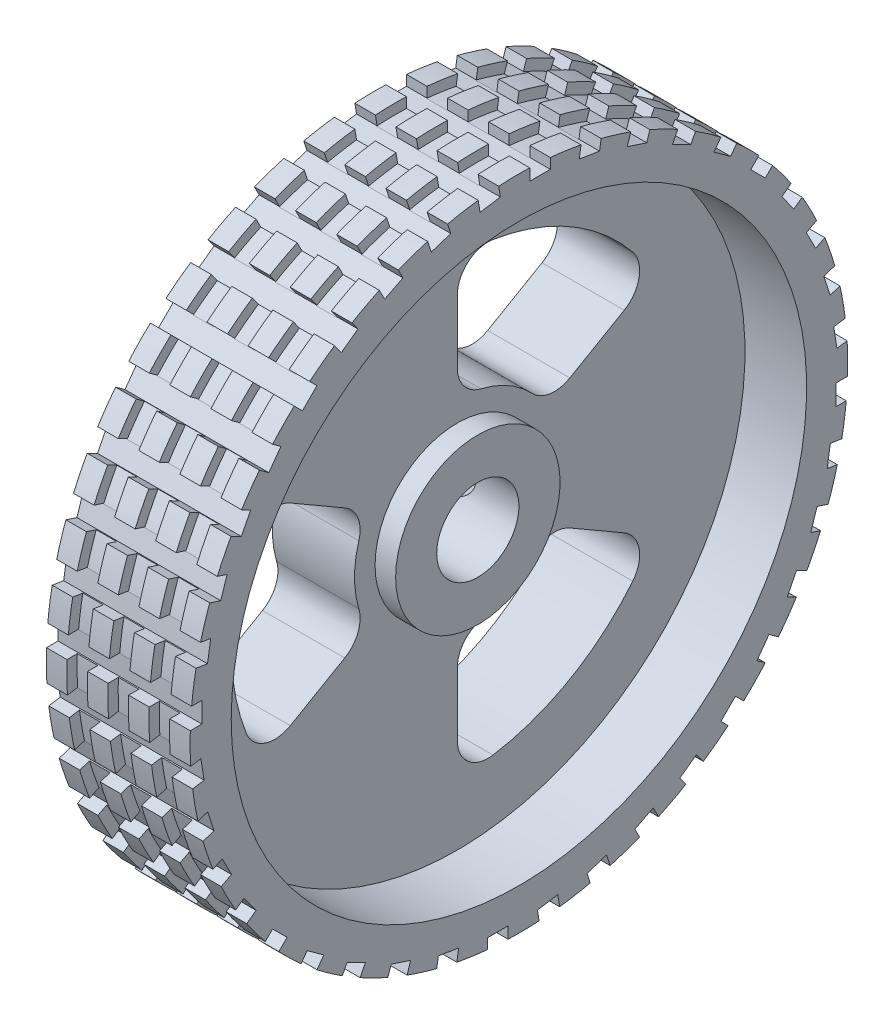
SolidWorks part; units mm, degrees
ref_plane "Front Plane" through (0, 0, 0) normal (0, 0, 1) x (1, 0, 0)
ref_plane "Top Plane" through (0, 0, 0) normal (0, 1, 0) x (1, 0, 0)
ref_plane "Right Plane" through (0, 0, 0) normal (1, 0, 0) x (0, 0, -1)
sketch "Sketch1" plane through (0, 0, 0) normal (0, 0, 1) x (1, 0, 0)
  line L0 (0, 0) -> (11.7914, 0) construction
  line L1 (0, 2) -> (5, 2)
  line L2 (5, 2) -> (5, 4)
  line L3 (5, 4) -> (4, 4)
  line L4 (4, 4) -> (4, 14)
  line L5 (4, 14) -> (7, 14)
  line L6 (7, 14) -> (7, 16)
  line L7 (7, 16) -> (0, 16)
  line L8 (0, 16) -> (0, 2)
  dimension "D1" = 7
  dimension "D2" = 4
  dimension "D3" = 4
  dimension "D4" = 8
  dimension "D5" = 5
  dimension "D6" = 28
  dimension "D7" = 32
revolve "Revolve1" add sketch "Sketch1" angle 360 about L0
sketch "Sketch2" plane through (0, 0, 0) normal (0, 1, 0) x (1, 0, 0)
  line L0 (2, 0) -> (2, 16) construction
  line L1 (7, 16) -> (0, 16) construction
  line L2 (2.9, 0) -> (2.9, 11.5)
  line L3 (0, 0) -> (7, 0) construction
  line L4 (7, -16) -> (7, 16) construction
  line L5 (2.9, 11.5) -> (3.5, 11.5)
  line L6 (3.5, 11.5) -> (3.5, 16)
  line L7 (7, 16) -> (0, 16) construction
  line L8 (3.5, 16) -> (2, 16)
  line L9 (2, 16) -> (2, 0)
  line L10 (0, 16) -> (0, -16) construction
  line L11 (2, 0) -> (2, 19.1764) construction
  line L12 (2, 0) -> (2.9, 0)
  dimension "D1" = 4.5
  dimension "D2" = 2
  dimension "D3" = 3
  dimension "D4" = 1.8
revolve "Cut-Revolve1" cut sketch "Sketch2" angle 360 about L9
sketch "Sketch4" plane through (4, 0, 0) normal (1, 0, 0) x (0, 0, -1)
  line L0 (-8.124, 4.6904) -> (-5.4772, 3.1623)
  line L1 (-8.124, -4.6904) -> (-5.4772, -3.1623)
  line L2 (0, 0) -> (-18.7263, 0) construction
  line L3 (0, 3.85) -> (0, -3.85) construction
  arc A0 (-10.2752, 3.9269) -> (-10.2752, -3.9269) centre (0, 0) ccw
  arc A2 (-10.2752, -3.9269) -> (-8.124, -4.6904) centre (-8.874, -3.3914) ccw
  circle A3 centre (0, 0) radius 5
  arc A4 (-4.7902, 1.4333) -> (-4.7902, -1.4333) centre (0, 0) ccw
  arc A5 (-10.2752, 3.9269) -> (-8.124, 4.6904) centre (-8.874, 3.3914) cw
  arc A6 (-5.4772, -3.1623) -> (-4.7902, -1.4333) centre (-6.2272, -1.8632) ccw
  arc A7 (-5.4772, 3.1623) -> (-4.7902, 1.4333) centre (-6.2272, 1.8632) cw
  point P16 (0, 5)
  dimension "D2" = 1.5
  dimension "D4" = 11
  dimension "D3" = 90
  dimension "D5" = 60
  dimension "D1" = 1
extrude "Cut-Extrude1" cut sketch "Sketch4" against normal through all
pattern_circular "CirPattern1" count 3 over 360 about axis through (0, 0, 0) along (1, 0, 0) of "Cut-Extrude1"
sketch "Sketch5" plane through (7, 0, 0) normal (1, 0, 0) x (0, 0, -1)
  line L0 (1.5273, 15.9269) -> (1.5273, 15.4269)
  line L1 (1.5273, 15.4269) -> (0.5273, 15.4269)
  line L2 (0.5273, 15.4269) -> (0.5273, 15.9913)
  circle A1 centre (0, 0) radius 16 construction
  arc A2 (0.5273, 15.9913) -> (1.5273, 15.9269) centre (0, 0) cw
  dimension "D1" = 0.5
  dimension "D2" = 1
extrude "Cut-Extrude2" cut sketch "Sketch5" against normal through all
pattern_circular "CirPattern2" count 40 over 360 about axis through (0, 0, 0) along (1, 0, 0) of "Cut-Extrude2"
sketch "Sketch6" plane through (0, 0, 0) normal (0, 0, 1) x (1, 0, 0)
  line L0 (7, 16) -> (0, 16) construction
  line L1 (5, 16) -> (6, 16)
  line L2 (5, 16) -> (5, 15.5)
  line L3 (5, 15.5) -> (6, 15.5)
  line L4 (6, 16) -> (6, 15.5)
  line L5 (0, 0) -> (15.2329, 0) construction
  line L6 (7, 15.6194) -> (7, 15.8769) construction
  dimension "D1" = 0.5
  dimension "D2" = 1
  dimension "D3" = 1
revolve "Cut-Revolve2" cut sketch "Sketch6" angle 360 about L5
pattern_linear "LPattern1" count 3 spacing 2 along (-1, 0, 0) of "Cut-Revolve2"
